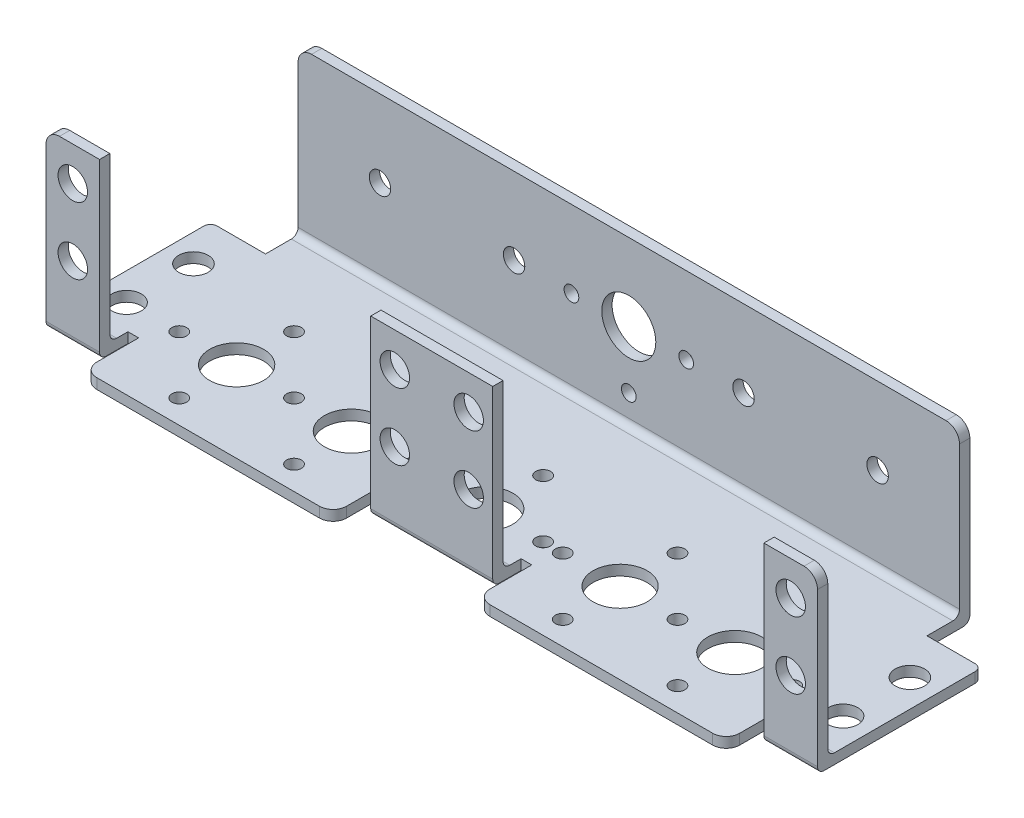
SolidWorks part; units mm, degrees
material "1060 Alloy"
ref_plane "Front" through (0, 0, 0) normal (0, 0, 1) x (1, 0, 0)
ref_plane "Top" through (0, 0, 0) normal (0, 1, 0) x (1, 0, 0)
ref_plane "Right" through (0, 0, 0) normal (1, 0, 0) x (0, 0, -1)
sketch "Sketch1" plane through (0, 0, 0) normal (0, 1, 0) x (1, 0, 0)
  line L0 (-57.15, 17.36) -> (57.15, 17.36)
  line L1 (57.15, 17.36) -> (57.15, -17.36)
  line L2 (-57.15, -17.36) -> (57.15, -17.36)
  line L3 (-57.15, -17.36) -> (-57.15, 17.36)
  line L4 (0, 17.36) -> (0, -17.36) construction
  point P6 (0, 0)
  dimension "D1" = 114.3
  dimension "D2" = 34.72
extrude "Boss-Extrude1" add sketch "Sketch1" along normal blind 1.524
ref_plane "Plane1" through (0, 1.524, 0) normal (0, 1, 0) x (1, 0, 0)
sketch "Sketch2" plane through (0, 1.524, 0) normal (0, 1, 0) x (1, 0, 0)
  line L0 (-49, 17.36) -> (-49, 11.01)
  line L1 (57.15, 17.36) -> (-57.15, 17.36) construction
  line L2 (-49, 11.01) -> (-57.15, 11.01)
  line L3 (-57.15, 17.36) -> (-57.15, -17.36) construction
  line L4 (-57.15, 11.01) -> (-57.15, 17.36)
  line L5 (-57.15, 17.36) -> (-49, 17.36)
  line L6 (-53.075, 11.01) -> (-53.075, -17.36) construction
  line L7 (-57.15, -17.36) -> (57.15, -17.36) construction
  line L8 (-57.15, -13.36) -> (-49.2125, -13.36)
  line L9 (-47.625, -13.36) -> (-47.625, -17.36)
  line L10 (-47.625, -17.36) -> (-57.15, -17.36)
  line L11 (-57.15, -13.36) -> (-57.15, -17.36)
  line L12 (-47.625, -13.36) -> (-47.625, -9.16)
  line L13 (-47.625, -9.16) -> (-49.2125, -9.16)
  line L14 (-49.2125, -9.16) -> (-49.2125, -13.36)
  line L15 (0, 17.36) -> (0, -17.36) construction
  line L16 (-10.625, -13.36) -> (-10.625, -9.16)
  line L17 (-10.625, -9.16) -> (-9.0375, -9.16)
  line L18 (-9.0375, -9.16) -> (-9.0375, -13.36)
  line L19 (-9.0375, -13.36) -> (0, -13.36)
  line L20 (-10.625, -13.36) -> (-10.625, -17.36)
  line L21 (-10.625, -17.36) -> (0, -17.36)
  line L23 (-47.625, -13.36) -> (-9.0375, -13.36) construction
  line L24 (0, -13.36) -> (0, -17.36)
  circle A0 centre (-53.075, 4.41) radius 2.184
  circle A1 centre (-53.075, -5.5) radius 2.184
  dimension "D3" = 4.368
  dimension "D1" = 8.15
  dimension "D2" = 6.35
  dimension "D4" = 9.91
  dimension "D5" = 6.6
  dimension "D6" = 4
  dimension "D7" = 9.525
  dimension "D8" = 1.5875
  dimension "D9" = 8.2
  dimension "D10" = 1.5875
  dimension "D11" = 37
  dimension "D12" = 4
extrude "Cut-Extrude1" cut sketch "Sketch2" against normal up to surface (1.524 mm away) up to face at (0, 0, 0)
mirror "Mirror1" about plane through (0, 0, 0) normal (1, 0, 0) of "Cut-Extrude1"
sketch "Sketch3" plane through (0, 1.524, 0) normal (0, 1, 0) x (1, 0, 0)
  line L0 (-47.625, -17.36) -> (-10.625, -17.36) construction
  line L1 (-57.15, 11.01) -> (-57.15, -13.36) construction
  circle A0 centre (-36.9062, -5.36) radius 4
  dimension "D1" = 8
  dimension "D3" = 20.2438
  dimension "D2" = 12
extrude "Cut-Extrude2" cut sketch "Sketch3" against normal mid plane 100
sketch "Sketch4" plane through (0, 1.524, 0) normal (0, 1, 0) x (1, 0, 0)
  line L0 (49, 17.36) -> (-49, 17.36) construction
  circle A0 centre (-36.9062, 3.14) radius 1.09
  circle A1 centre (-36.9062, -5.36) radius 4 construction
  dimension "D1" = 2.18
  dimension "D2" = 8.5
  dimension "D3" = 14.22
extrude "Cut-Extrude3" cut sketch "Sketch4" against normal mid plane 100
pattern_circular "CirPattern1" count 4 over 360 about axis through (-36.9062, 0, 5.36) along (0, 1, 0) of "Cut-Extrude3"
sketch "Sketch6" plane through (0, 1.524, 0) normal (0, 1, 0) x (1, 0, 0)
  line L0 (-28.4062, -4.27) -> (-28.4062, -17.36) construction
  line L1 (-47.625, -17.36) -> (-10.625, -17.36) construction
  line L3 (-57.15, 11.01) -> (-57.15, -13.36) construction
  circle A0 centre (-28.4062, -5.36) radius 1.09 construction
  dimension "D1" = 28.7438
ref_plane "Plane2" through (-28.4062, 0, 0) normal (-1, 0, 0) x (0, 0, 1)
mirror "Mirror2" about plane through (-28.4062, 0, 0) normal (-1, 0, 0) of "CirPattern1", "Cut-Extrude2", "Cut-Extrude3"
sketch "Sketch7" plane through (0, 1.524, 0) normal (0, 1, 0) x (1, 0, 0)
  line L0 (0, 17.36) -> (0, -13.36) construction
  line L1 (49, 17.36) -> (-49, 17.36) construction
  line L2 (9.0375, -13.36) -> (-9.0375, -13.36) construction
  line L3 (-23.9062, -5.36) -> (0, -5.36) construction
  circle A0 centre (-19.9062, -5.36) radius 4 construction
  circle A1 centre (0, -5.36) radius 4
  dimension "D1" = 5.36
extrude "Cut-Extrude4" cut sketch "Sketch7" against normal blind 100
sketch "Sketch8" plane through (0, 1.524, 0) normal (0, 1, 0) x (1, 0, 0)
  line L0 (0, -9.36) -> (0, 3.14) construction
  circle A0 centre (0, -5.36) radius 4 construction
  circle A1 centre (0, 3.14) radius 1.09
  dimension "D1" = 2.18
  dimension "D2" = 8.5
extrude "Cut-Extrude5" cut sketch "Sketch8" against normal blind 100
pattern_circular "CirPattern2" count 4 over 360 about axis through (0, 0, 5.36) along (0, 1, 0) skipping 2 of "Cut-Extrude5"
mirror "Mirror3" about plane through (0, 0, 0) normal (1, 0, 0) of "Mirror2", "Cut-Extrude3", "CirPattern1", "Cut-Extrude2"
sketch "Sketch9" plane through (0, 1.524, 0) normal (0, 1, 0) x (1, 0, 0)
  line L0 (-57.15, -13.36) -> (-57.15, -11.836)
  line L1 (-57.15, 11.01) -> (-57.15, -13.36) construction
  line L2 (-57.15, -11.836) -> (-49.2125, -11.836)
  line L3 (-49.2125, -9.16) -> (-49.2125, -13.36) construction
  line L4 (-49.2125, -11.836) -> (-49.2125, -13.36)
  line L5 (-49.2125, -13.36) -> (-57.15, -13.36)
  dimension "D1" = 1.524
extrude "Boss-Extrude2" add sketch "Sketch9" along normal blind 24.2
mirror "Mirror4" about plane through (0, 0, 0) normal (1, 0, 0) of "Boss-Extrude2"
sketch "Sketch10" plane through (0, 1.524, 0) normal (0, 1, 0) x (1, 0, 0)
  line L0 (-49, 17.36) -> (49, 17.36)
  line L1 (49, 17.36) -> (49, 15.836)
  line L2 (49, 11.01) -> (49, 17.36) construction
  line L3 (49, 15.836) -> (-49, 15.836)
  line L4 (-49, 11.01) -> (-49, 17.36) construction
  line L5 (-49, 15.836) -> (-49, 17.36)
  line L6 (-9.0375, -13.36) -> (9.0375, -13.36)
  line L7 (-9.0375, -13.36) -> (-9.0375, -11.836)
  line L9 (-9.0375, -13.36) -> (-9.0375, -9.16) construction
  line L11 (-9.0375, -11.836) -> (9.0375, -11.836)
  line L12 (9.0375, -13.36) -> (9.0375, -9.16) construction
  line L13 (9.0375, -11.836) -> (9.0375, -13.36)
  dimension "D1" = 1.524
  dimension "D2" = 1.524
extrude "Boss-Extrude3" add sketch "Sketch10" along normal blind 24.2
ref_plane "Plane3" through (0, 0, 13.36) normal (0, 0, 1) x (1, 0, 0)
sketch "Sketch11" plane through (0, 0, 13.36) normal (0, 0, 1) x (1, 0, 0)
  line L0 (-53.1813, 25.724) -> (-53.1813, 0) construction
  line L1 (-57.15, 25.724) -> (-49.2125, 25.724) construction
  line L2 (-49.2125, 0) -> (-57.15, 0) construction
  circle A0 centre (-53.1813, 20.644) radius 2.1844
  circle A1 centre (-53.1813, 10.734) radius 2.1844
  dimension "D1" = 5.08
  dimension "D2" = 9.91
  dimension "D3" = 4.3688
extrude "Cut-Extrude6" cut sketch "Sketch11" against normal blind 24.2
mirror "Mirror5" about plane through (0, 0, 0) normal (1, 0, 0) of "Cut-Extrude6"
ref_plane "Plane4" through (0, 0, 13.36) normal (0, 0, 1) x (1, 0, 0)
sketch "Sketch12" plane through (0, 0, 13.36) normal (0, 0, 1) x (1, 0, 0)
  line L0 (0, 25.724) -> (0, 0) construction
  line L1 (-9.0375, 25.724) -> (9.0375, 25.724) construction
  circle A0 centre (-5.4713, 20.644) radius 2.1844
  circle A1 centre (-5.4713, 10.734) radius 2.1844
  circle A2 centre (-53.1812, 10.734) radius 2.1844 construction
  circle A3 centre (5.4713, 10.734) radius 2.1844
  circle A4 centre (5.4713, 20.644) radius 2.1844
  dimension "D1" = 4.3688
  dimension "D2" = 9.91
  dimension "D4" = 5.08
  dimension "D3" = 47.71
extrude "Cut-Extrude8" cut sketch "Sketch12" against normal blind 24.2
fillet "Fillet1" radius 1 10 edges at (-57.15, 0.762, -11.01) (57.15, 0.762, -11.01) (0, 0, -17.36) (0, 1.524, -15.836) (53.1813, 0, 13.36) (53.1813, 1.524, 11.836) (0, 1.524, 11.836) (0, 0, 13.36) (-53.1813, 1.524, 11.836) (-53.1813, 0, 13.36)
ref_plane "Plane5" through (0, 0, -15.836) normal (0, 0, 1) x (1, 0, 0)
sketch "Sketch13" plane through (0, 0, -15.836) normal (0, 0, 1) x (1, 0, 0)
  line L0 (10.625, 0) -> (47.625, 0) construction
  line L1 (0, 0) -> (0, 25.724) construction
  line L2 (-49, 25.724) -> (49, 25.724) construction
  line L4 (8.5, 2.524) -> (8.5, 25.724) construction
  line L5 (-49, 2.524) -> (49, 2.524) construction
  circle A0 centre (36.8628, 14.2875) radius 1.5875
  circle A1 centre (17, 14.2875) radius 1.5875
  dimension "D1" = 3.175
  dimension "D2" = 14.2875
  dimension "D3" = 8.5
  dimension "D4" = 19.8628
  dimension "D5" = 8.5
extrude "Cut-Extrude9" cut sketch "Sketch13" against normal blind 24.2
mirror "Mirror6" about plane through (0, 0, 0) normal (1, 0, 0) of "Cut-Extrude9"
fillet "Fillet2" radius 2 8 edges at (47.625, 0.762, 17.36) (10.625, 0.762, 17.36) (-10.625, 0.762, 17.36) (-47.625, 0.762, 17.36) (-49, 25.724, -16.598) (49, 25.724, -16.598) (57.15, 25.724, 12.598) (-57.15, 25.724, 12.598)
sketch "Sketch14" plane through (0, 0, -15.836) normal (0, 0, 1) x (1, 0, 0)
  line L0 (0, 25.724) -> (0, 0) construction
  line L1 (-47, 25.724) -> (47, 25.724) construction
  line L2 (38.4503, 14.2875) -> (0, 14.2875) construction
  circle A0 centre (36.8628, 14.2875) radius 1.5875 construction
  circle A1 centre (0, 14.2875) radius 4
  dimension "D1" = 8
  dimension "D2" = 14.2875
extrude "Cut-Extrude10" cut sketch "Sketch14" against normal blind 24.2
sketch "Sketch15" plane through (0, 0, -15.836) normal (0, 0, 1) x (1, 0, 0)
  circle A0 centre (0, 5.7875) radius 1.09
  circle A1 centre (0, 14.2875) radius 4 construction
  dimension "D1" = 2.18
  dimension "D2" = 8.5
  dimension "D3" = 5.7875
extrude "Cut-Extrude11" cut sketch "Sketch15" against normal blind 24.2
pattern_circular "CirPattern3" count 4 over 360 about axis through (0, 14.2875, 0) along (0, 0, 1) skipping 2 of "Cut-Extrude11"
